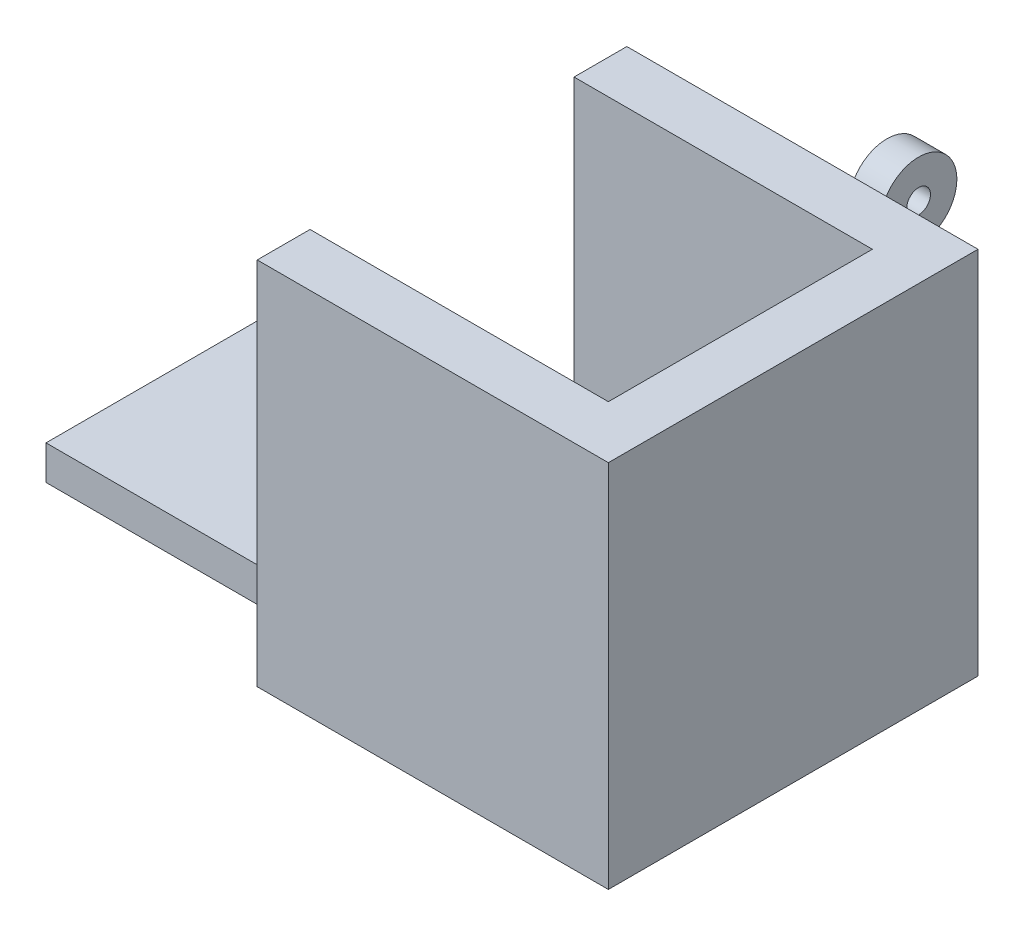
SolidWorks part; units mm, degrees
ref_plane "前基準面" through (0, 0, 0) normal (0, 0, 1) x (1, 0, 0)
ref_plane "上基準面" through (0, 0, 0) normal (0, 1, 0) x (1, 0, 0)
ref_plane "右基準面" through (0, 0, 0) normal (1, 0, 0) x (0, 0, -1)
sketch "草圖1" plane through (0, 0, 0) normal (0, 1, 0) x (1, 0, 0)
  line L1 (-66.5, 70) -> (66.5, 70)
  line L2 (-66.5, 70) -> (-66.5, -70)
  line L3 (-66.5, -70) -> (66.5, -70)
  line L4 (66.5, 70) -> (66.5, -70)
  line L5 (-66.5, 70) -> (66.5, -70) construction
  line L6 (-66.5, -70) -> (66.5, 70) construction
  point P0 (0, 0)
  dimension "D1" = 133
  dimension "D2" = 140
extrude "填料-伸長1" add sketch "草圖1" along normal blind 140
sketch "草圖2" plane through (0, 140, 0) normal (0, 1, 0) x (1, 0, 0)
  line L0 (-66.5, 70) -> (-66.5, -70) construction
  line L1 (-66.5, 50) -> (46.5, 50)
  line L2 (-66.5, 50) -> (-66.5, -50)
  line L3 (-66.5, -50) -> (46.5, -50)
  line L4 (46.5, 50) -> (46.5, -50)
  line L5 (66.5, 70) -> (-66.5, 70) construction
  line L6 (66.5, -70) -> (66.5, 70) construction
  line L7 (-66.5, -70) -> (66.5, -70) construction
  dimension "D1" = 20
  dimension "D2" = 20
  dimension "D3" = 20
extrude "除料-伸長1" cut sketch "草圖2" against normal blind 110
sketch "草圖3" plane through (-66.5, 0, 0) normal (-1, 0, 0) x (0, 0, 1)
  line L0 (50, 30) -> (-50, 30) construction
  line L1 (-50, 20) -> (50, 20)
  line L2 (-50, 20) -> (-50, 7)
  line L3 (-50, 7) -> (50, 7)
  line L4 (50, 20) -> (50, 7)
  line L5 (-70, 0) -> (70, 0) construction
  line L6 (-70, 140) -> (-70, 0) construction
  line L7 (70, 140) -> (70, 0) construction
  dimension "D1" = 10
  dimension "D2" = 7
  dimension "D3" = 20
  dimension "D4" = 20
extrude "填料-伸長2" add sketch "草圖3" along normal blind 100
sketch "草圖4" plane through (0, 20, 0) normal (0, 1, 0) x (1, 0, 0)
  line L0 (-66.5, 0) -> (-86.5, 0) construction
  line L1 (-66.5, -50) -> (-66.5, 50) construction
  circle A0 centre (-86.5, 0) radius 3
  dimension "D2" = 6
  dimension "D1" = 20
extrude "除料-伸長3" cut sketch "草圖4" against normal through all
sketch "草圖5" plane through (0, 0, -70) normal (0, 0, -1) x (-1, 0, 0)
  line L0 (-66.5, 140) -> (-66.5, 0) construction
  line L1 (-31.5, 132) -> (-19.5, 132)
  line L2 (-31.5, 132) -> (-31.5, 120)
  line L3 (-31.5, 120) -> (-19.5, 120)
  line L4 (-19.5, 132) -> (-19.5, 120)
  line L5 (-66.5, 140) -> (66.5, 140) construction
  dimension "D1" = 35
  dimension "D2" = 12
  dimension "D3" = 12
  dimension "D4" = 8
extrude "填料-伸長3" add sketch "草圖5" along normal blind 10
sketch "草圖6" plane through (31.5, 0, 0) normal (1, 0, 0) x (0, 0, -1)
  line L0 (80, 132) -> (82.5, 132) construction
  circle A0 centre (82.5, 132) radius 4.4909
  dimension "D1" = 2.5
extrude "伸長-薄件2" add sketch "草圖6" against normal blind 12 thin
sketch "草圖7" plane through (31.5, 0, 0) normal (1, 0, 0) x (0, 0, -1)
  circle A0 centre (82.5, 132) radius 4.4909
extrude "除料-伸長4" cut sketch "草圖7" against normal through all
